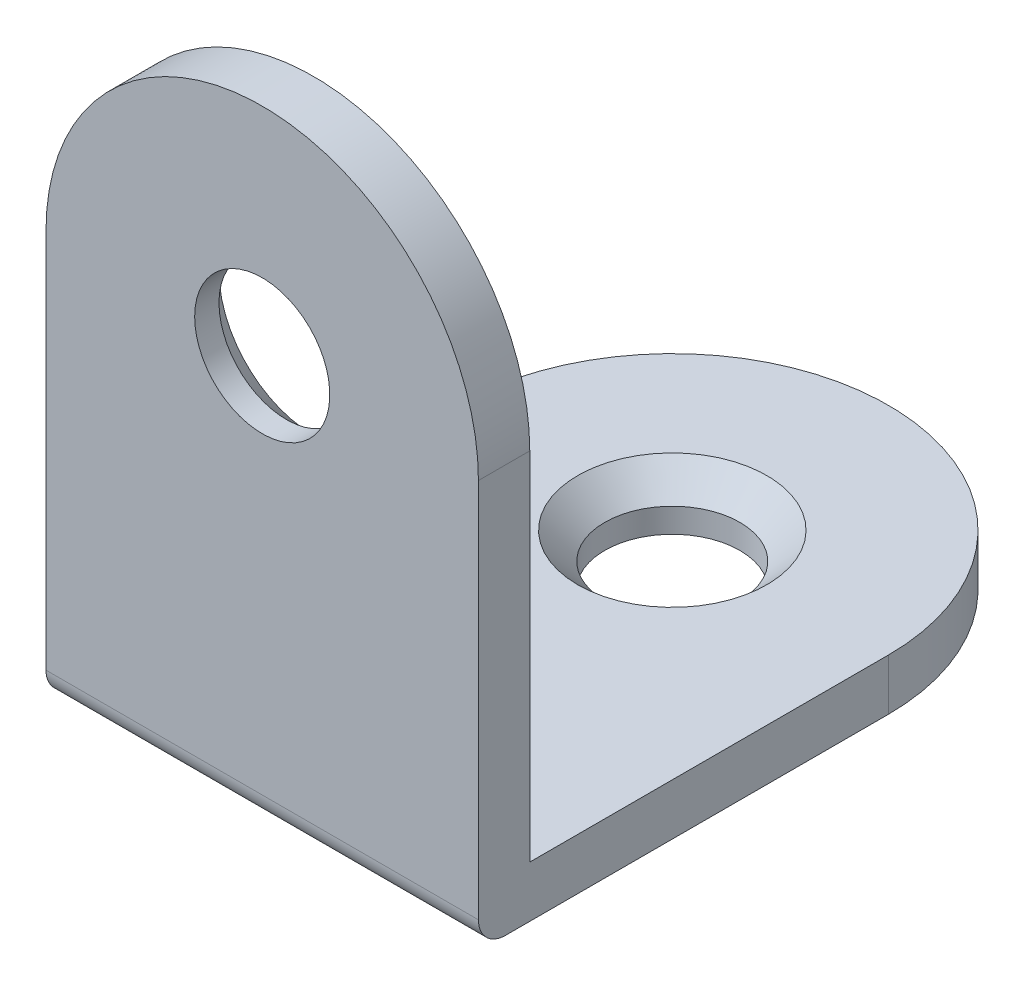
SolidWorks part; units mm, degrees
ref_plane "前视基准面" through (0, 0, 0) normal (0, 0, 1) x (1, 0, 0)
ref_plane "上视基准面" through (0, 0, 0) normal (0, 1, 0) x (1, 0, 0)
ref_plane "右视基准面" through (0, 0, 0) normal (1, 0, 0) x (0, 0, -1)
other "Configuration Table"
sketch "草图1" plane through (0, 0, 0) normal (0, 0, 1) x (1, 0, 0)
  line L0 (0, 0) -> (16, 0)
  line L1 (16, 0) -> (16, 15.0763)
  line L2 (16, 23.0763) -> (0, 23.0763) construction
  line L3 (0, 15.0763) -> (0, -1.6587)
  line L4 (0, 7.0763) -> (16, 7.0763) construction
  line L5 (0, 23.0763) -> (16, 7.0763) construction
  line L6 (16, 23.0763) -> (0, 7.0763) construction
  arc A0 (16, 15.0763) -> (0, 15.0763) centre (8, 15.0763) ccw
  circle A1 centre (8, 15.0763) radius 2.5
  dimension "D1" = 16
extrude "凸台-拉伸1" add sketch "草图1" along normal blind 1.9 contours L1 A0 L3 L0 A1
sketch "草图3" plane through (0, 0, 0) normal (0, 1, 0) x (1, 0, 0)
  line L0 (0, -1.9) -> (16, -1.9)
  line L1 (16, -1.9) -> (16, 13.2727)
  line L2 (16, 21.2727) -> (0, 21.2727) construction
  line L3 (0, 13.2727) -> (0, -1.9)
  line L4 (0, 5.2727) -> (16, 5.2727) construction
  line L5 (0, 21.2727) -> (16, 5.2727) construction
  line L6 (16, 21.2727) -> (0, 5.2727) construction
  line L7 (0, -1.9) -> (16, -1.9) construction
  line L9 (16, -1.9) -> (16, 0) construction
  arc A0 (16, 13.2727) -> (0, 13.2727) centre (8, 13.2727) ccw
  circle A1 centre (8, 13.2727) radius 2.5
extrude "凸台-拉伸2" add sketch "草图3" along normal blind 1.9
fillet "圆角1" radius 1 1 edges at (8, 0, 1.9)
chamfer "倒角1" distance 1 angle 45 2 edges at (8, 1.9, -10.7727) (10.5, 15.0763, 0)
